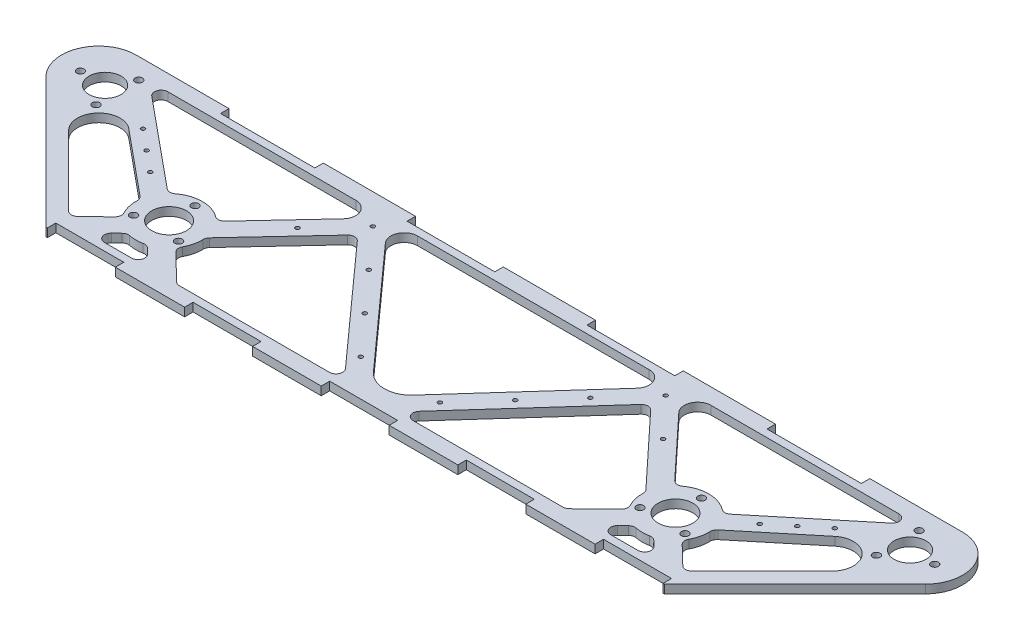
SolidWorks part; units mm, degrees
material "6061-T6 (SS)"
ref_plane "Alzado" through (0, 0, 0) normal (0, 0, 1) x (1, 0, 0)
ref_plane "Planta" through (0, 0, 0) normal (0, 1, 0) x (1, 0, 0)
ref_plane "Vista lateral" through (0, 0, 0) normal (1, 0, 0) x (0, 0, -1)
sketch "Sketch1" plane through (0, 0, 0) normal (0, 1, 0) x (1, 0, 0)
  line L0 (-232.01, 0) -> (232.01, 0)
  line L1 (-232.01, 0) -> (-329.8939, 97.8839)
  line L2 (-310.0879, 145.7) -> (310.0879, 145.7)
  line L3 (329.8939, 97.8839) -> (232.01, 0)
  line L4 (-310.0879, 135.7) -> (310.0879, 135.7) construction
  line L5 (322.8229, 104.955) -> (227.8679, 10) construction
  line L6 (-227.8679, 10) -> (227.8679, 10) construction
  line L7 (-227.8679, 10) -> (-322.8229, 104.955) construction
  arc A0 (310.0879, 145.7) -> (329.8939, 97.8839) centre (310.0879, 117.69) cw
  arc A1 (-329.8939, 97.8839) -> (-310.0879, 145.7) centre (-310.0879, 117.69) cw
  arc A2 (310.0879, 135.7) -> (322.8229, 104.955) centre (310.0879, 117.69) cw construction
  arc A3 (-322.8229, 104.955) -> (-310.0879, 135.7) centre (-310.0879, 117.69) cw construction
  point P4 (0, 0)
  dimension "D4" = 28.01
  dimension "D1" = 45
  dimension "D2" = 464.02
  dimension "D3" = 145.7
  dimension "D5" = 10
extrude "Boss-Extrude1" add sketch "Sketch1" along normal blind 6.35
sketch "Sketch2" plane through (0, 6.35, 0) normal (0, 1, 0) x (1, 0, 0)
  line L0 (310.0879, 145.7) -> (-310.0879, 145.7) construction
  line L1 (0, 0) -> (0, 145.7) construction
  line L2 (-232.01, 0) -> (232.01, 0) construction
  circle A0 centre (-302.0235, 114.35) radius 12
  circle A2 centre (-190, 50.35) radius 13
  circle A5 centre (-302.0235, 114.35) radius 18.5 construction
  circle A6 centre (-190, 50.35) radius 19.5 construction
  circle A7 centre (-320.5235, 114.35) radius 2.75
  circle A8 centre (-292.7735, 130.3715) radius 2.75
  circle A9 centre (-292.7735, 98.3285) radius 2.75
  circle A11 centre (-190, 69.85) radius 2.75
  circle A12 centre (-173.1125, 40.6) radius 2.75
  circle A13 centre (-206.8875, 40.6) radius 2.75
  circle A14 centre (190, 50.35) radius 19.5 construction
  circle A15 centre (302.0235, 114.35) radius 18.5 construction
  circle A16 centre (206.8875, 40.6) radius 2.75
  circle A17 centre (173.1125, 40.6) radius 2.75
  circle A18 centre (190, 69.85) radius 2.75
  circle A19 centre (292.7735, 98.3285) radius 2.75
  circle A20 centre (292.7735, 130.3715) radius 2.75
  circle A21 centre (320.5235, 114.35) radius 2.75
  circle A22 centre (190, 50.35) radius 13
  circle A23 centre (302.0235, 114.35) radius 12
  point P29 (-190, 50.35)
  point P30 (-302.0235, 114.35)
  point P49 (302.0235, 114.35)
  point P50 (190, 50.35)
  dimension "D3" = 24
  dimension "D6" = 26
  dimension "D7" = 37
  dimension "D8" = 39
  dimension "D9" = 5.5
  dimension "D11" = 3
  dimension "D2" = 31.35
  dimension "D4" = 50.35
  dimension "D5" = 42.01
  dimension "D12" = 604.047
  dimension "D10" = 3
extrude "Cut-Extrude1" cut sketch "Sketch2" against normal blind 10
sketch "Sketch4" plane through (0, 6.35, 0) normal (0, 1, 0) x (1, 0, 0)
  line L12 (229.3797, 6.35) -> (325.4038, 102.3741)
  line L13 (310.0879, 139.35) -> (-310.0879, 139.35)
  line L14 (-325.4038, 102.3741) -> (-229.3797, 6.35)
  line L15 (-229.3797, 6.35) -> (229.3797, 6.35)
  line L16 (229.3797, 6.35) -> (325.4038, 102.3741) construction
  line L17 (310.0879, 139.35) -> (-310.0879, 139.35) construction
  line L18 (-325.4038, 102.3741) -> (-229.3797, 6.35) construction
  line L19 (-229.3797, 6.35) -> (229.3797, 6.35) construction
  arc A6 (325.4038, 102.3741) -> (310.0879, 139.35) centre (310.0879, 117.69) ccw
  arc A7 (-310.0879, 139.35) -> (-325.4038, 102.3741) centre (-310.0879, 117.69) ccw
  arc A8 (325.4038, 102.3741) -> (310.0879, 139.35) centre (310.0879, 117.69) ccw construction
  arc A9 (-310.0879, 139.35) -> (-325.4038, 102.3741) centre (-310.0879, 117.69) ccw construction
  dimension "D1" = 6.35
sketch "Sketch3" plane through (0, 6.35, 0) normal (0, 1, 0) x (1, 0, 0)
  line L0 (-203.6098, 20.5948) -> (-199.5103, 24.558)
  line L1 (-180.4897, 24.558) -> (-176.3902, 20.5948)
  line L2 (-216.7974, 55.3714) -> (-264.9333, 95.0444)
  line L3 (-226.9661, 18.8783) -> (-212.9059, 32.4713)
  line L4 (-211.3773, 70.3424) -> (-277.5023, 124.8416)
  line L5 (-274.3223, 133.7) -> (-133.2758, 133.7)
  line L6 (-168.6307, 71.1511) -> (-125.9643, 116.8778)
  line L7 (0, 12) -> (0, 133.7) construction
  line L8 (-94.3432, 117.0171) -> (-14.878, 28.5613)
  line L9 (227.0394, 12) -> (321.4087, 106.3692)
  line L10 (310.0879, 133.7) -> (-310.0879, 133.7)
  line L11 (-321.4087, 106.3692) -> (-227.0394, 12)
  line L12 (-227.0394, 12) -> (227.0394, 12)
  line L13 (227.0394, 12) -> (321.4087, 106.3692) construction
  line L14 (310.0879, 133.7) -> (133.2758, 133.7) construction
  line L15 (-321.4087, 106.3692) -> (-227.0394, 12) construction
  line L16 (-227.0394, 12) -> (227.0394, 12) construction
  line L17 (-167.0941, 32.4713) -> (-147.3727, 13.4052)
  line L18 (-163.6645, 54.4864) -> (-113.7257, 108.0071)
  line L19 (-106.3504, 107.9375) -> (-27.6576, 20.3415)
  line L20 (-286.4232, 71.3837) -> (-233.977, 18.9375)
  line L21 (-200.1345, 12) -> (-179.8655, 12)
  line L22 (-143.8974, 12) -> (-31.3771, 12)
  line L23 (-86.9042, 133.7) -> (86.9042, 133.7)
  line L24 (143.8974, 12) -> (31.3771, 12)
  line L25 (200.1345, 12) -> (179.8655, 12)
  line L26 (286.4232, 71.3837) -> (233.977, 18.9375)
  line L27 (106.3504, 107.9375) -> (27.6576, 20.3415)
  line L28 (163.6645, 54.4864) -> (113.7257, 108.0071)
  line L29 (167.0941, 32.4713) -> (147.3727, 13.4052)
  line L30 (94.3432, 117.0171) -> (14.878, 28.5613)
  line L31 (168.6307, 71.1511) -> (125.9643, 116.8778)
  line L32 (274.3223, 133.7) -> (133.2758, 133.7)
  line L33 (211.3773, 70.3424) -> (277.5023, 124.8416)
  line L34 (226.9661, 18.8783) -> (212.9059, 32.4713)
  line L35 (216.7974, 55.3714) -> (264.9333, 95.0444)
  line L36 (180.4897, 24.558) -> (176.3902, 20.5948)
  line L37 (203.6098, 20.5948) -> (199.5103, 24.558)
  line L38 (-133.2758, 133.7) -> (-310.0879, 133.7) construction
  line L39 (86.9042, 133.7) -> (-86.9042, 133.7) construction
  arc A0 (-214.9812, 51.3192) -> (-211.9843, 38.4467) centre (-190, 50.35) ccw
  arc A1 (-264.9333, 95.0444) -> (-286.4232, 71.3837) centre (-275.1095, 82.6975) ccw
  arc A2 (-277.5023, 124.8416) -> (-274.3223, 133.7) centre (-274.3223, 128.7) cw
  arc A3 (-175.2387, 70.5268) -> (-205.1644, 70.2256) centre (-190, 50.35) ccw
  arc A4 (321.4087, 106.3692) -> (310.0879, 133.7) centre (310.0879, 117.69) ccw
  arc A5 (-310.0879, 133.7) -> (-321.4087, 106.3692) centre (-310.0879, 117.69) ccw
  arc A6 (321.4087, 106.3692) -> (310.0879, 133.7) centre (310.0879, 117.69) ccw construction
  arc A7 (-310.0879, 133.7) -> (-321.4087, 106.3692) centre (-310.0879, 117.69) ccw construction
  arc A8 (-168.0157, 38.4467) -> (-165.0073, 50.9544) centre (-190, 50.35) ccw
  arc A9 (-195.0292, 25.8611) -> (-184.9708, 25.8611) centre (-190, 50.35) ccw
  arc A10 (195.0292, 25.8611) -> (184.9708, 25.8611) centre (190, 50.35) cw
  arc A11 (168.0157, 38.4467) -> (165.0073, 50.9544) centre (190, 50.35) cw
  arc A12 (175.2387, 70.5268) -> (205.1644, 70.2256) centre (190, 50.35) cw
  arc A13 (277.5023, 124.8416) -> (274.3223, 133.7) centre (274.3223, 128.7) ccw
  arc A14 (264.9333, 95.0444) -> (286.4232, 71.3837) centre (275.1095, 82.6975) cw
  arc A15 (214.9812, 51.3192) -> (211.9843, 38.4467) centre (190, 50.35) cw
  arc A16 (-133.2758, 133.7) -> (-125.9643, 116.8778) centre (-133.2758, 123.7) cw
  arc A17 (-94.3432, 117.0171) -> (-86.9042, 133.7) centre (-86.9042, 123.7) cw
  arc A18 (94.3432, 117.0171) -> (86.9042, 133.7) centre (86.9042, 123.7) ccw
  arc A19 (125.9643, 116.8778) -> (133.2758, 133.7) centre (133.2758, 123.7) cw
  arc A20 (-175.2387, 70.5268) -> (-168.6307, 71.1511) centre (-172.2865, 74.5622) ccw
  arc A21 (-211.3773, 70.3424) -> (-205.1644, 70.2256) centre (-208.1973, 74.2008) ccw
  arc A22 (-216.7974, 55.3714) -> (-214.9812, 51.3192) centre (-219.9774, 51.513) cw
  arc A23 (-212.9059, 32.4713) -> (-211.9843, 38.4467) centre (-216.3812, 36.066) ccw
  arc A24 (-226.9661, 18.8783) -> (-233.977, 18.9375) centre (-230.4414, 22.4731) cw
  arc A25 (-203.6098, 20.5948) -> (-200.1345, 12) centre (-200.1345, 17) ccw
  arc A26 (-199.5103, 24.558) -> (-195.0292, 25.8611) centre (-196.035, 20.9633) cw
  arc A27 (-180.4897, 24.558) -> (-184.9708, 25.8611) centre (-183.965, 20.9633) ccw
  arc A28 (-176.3902, 20.5948) -> (-179.8655, 12) centre (-179.8655, 17) cw
  arc A29 (-113.7257, 108.0071) -> (-106.3504, 107.9375) centre (-110.0699, 104.596) cw
  arc A30 (-163.6645, 54.4864) -> (-165.0073, 50.9544) centre (-160.0088, 51.0753) ccw
  arc A31 (-167.0941, 32.4713) -> (-168.0157, 38.4467) centre (-163.6188, 36.066) cw
  arc A32 (-147.3727, 13.4052) -> (-143.8974, 12) centre (-143.8974, 17) ccw
  arc A33 (179.8655, 12) -> (176.3902, 20.5948) centre (179.8655, 17) cw
  arc A34 (184.9708, 25.8611) -> (180.4897, 24.558) centre (183.965, 20.9633) ccw
  arc A35 (195.0292, 25.8611) -> (199.5103, 24.558) centre (196.035, 20.9633) cw
  arc A36 (200.1345, 12) -> (203.6098, 20.5948) centre (200.1345, 17) ccw
  arc A37 (233.977, 18.9375) -> (226.9661, 18.8783) centre (230.4414, 22.4731) cw
  arc A38 (214.9812, 51.3192) -> (216.7974, 55.3714) centre (219.9774, 51.513) cw
  arc A39 (211.9843, 38.4467) -> (212.9059, 32.4713) centre (216.3812, 36.066) ccw
  arc A40 (175.2387, 70.5268) -> (168.6307, 71.1511) centre (172.2865, 74.5622) cw
  arc A41 (205.1644, 70.2256) -> (211.3773, 70.3424) centre (208.1973, 74.2008) ccw
  arc A42 (106.3504, 107.9375) -> (113.7257, 108.0071) centre (110.0699, 104.596) cw
  arc A43 (165.0073, 50.9544) -> (163.6645, 54.4864) centre (160.0088, 51.0753) ccw
  arc A44 (168.0157, 38.4467) -> (167.0941, 32.4713) centre (163.6188, 36.066) cw
  arc A45 (143.8974, 12) -> (147.3727, 13.4052) centre (143.8974, 17) ccw
  arc A46 (31.3771, 12) -> (27.6576, 20.3415) centre (31.3771, 17) cw
  arc A47 (-27.6576, 20.3415) -> (-31.3771, 12) centre (-31.3771, 17) cw
  arc A49 (-14.878, 28.5613) -> (14.878, 28.5613) centre (0, 41.9271) ccw
  point P72 (-171.9247, 67.6209)
  point P75 (-208.0753, 67.6209)
  point P78 (-214.774, 53.7038)
  point P81 (-209.9698, 35.3098)
  point P84 (-230.5007, 15.4612)
  point P87 (-212.5, 12)
  point P90 (-197.5, 26.5015)
  point P93 (-182.5, 26.5015)
  point P96 (-167.5, 12)
  point P99 (-110, 112)
  point P102 (-165.1318, 52.9138)
  point P105 (-170.0302, 35.3098)
  point P108 (-145.9191, 12)
  point P111 (167.5, 12)
  point P114 (182.5, 26.5015)
  point P117 (197.5, 26.5015)
  point P120 (212.5, 12)
  point P123 (230.5007, 15.4612)
  point P126 (214.774, 53.7038)
  point P129 (209.9698, 35.3098)
  point P132 (171.9247, 67.6209)
  point P135 (208.0753, 67.6209)
  point P138 (110, 112)
  point P141 (165.1318, 52.9138)
  point P144 (170.0302, 35.3098)
  point P147 (145.9191, 12)
  point P150 (20.164, 12)
  point P153 (-20.164, 12)
  dimension "D2" = 50
  dimension "D3" = 5
  dimension "D4" = 15
  dimension "D11" = 18.394
  dimension "D8" = 16
  dimension "D15" = 10
  dimension "D16" = 10
  dimension "D17" = 10
  dimension "D18" = 10
  dimension "D20" = 5
  dimension "D21" = 20
  dimension "D5" = 15
  dimension "D6" = 15
  dimension "D7" = 45
  dimension "D9" = 220
  dimension "D10" = 15
  dimension "D12" = 15
  dimension "D13" = 15
  dimension "D14" = 65
  dimension "D19" = 100
  dimension "D1" = 12
extrude "Cut-Extrude4" cut sketch "Sketch3" against normal blind 10
sketch "Sketch5" plane through (0, 6.35, 0) normal (0, 1, 0) x (1, 0, 0)
  line L0 (-232.01, 0) -> (232.01, 0) construction
  line L1 (-231.01, 0) -> (232.01, 0) construction
  line L2 (-231.01, 0) -> (-231.01, 6.36) construction
  line L3 (-231.01, 6.36) -> (232.01, 6.36) construction
  line L4 (232.01, 0) -> (232.01, 6.36) construction
  line L5 (-231.01, 6.36) -> (-180.01, 6.36)
  line L6 (-231.01, 6.36) -> (-231.01, 0)
  line L7 (-231.01, 0) -> (-180.01, 0)
  line L8 (-180.01, 6.36) -> (-180.01, 0)
  line L9 (-25.5, 6.36) -> (25.5, 6.36)
  line L10 (-25.5, 6.36) -> (-25.5, 0)
  line L11 (-25.5, 0) -> (25.5, 0)
  line L12 (25.5, 6.36) -> (25.5, 0)
  line L13 (-128.01, 6.36) -> (-77.01, 6.36)
  line L14 (-128.01, 6.36) -> (-128.01, 0)
  line L15 (-128.01, 0) -> (-77.01, 0)
  line L16 (-77.01, 6.36) -> (-77.01, 0)
  line L17 (0, 0) -> (0, 6.36) construction
  line L23 (77.01, 6.36) -> (128.01, 6.36)
  line L24 (77.01, 6.36) -> (77.01, 0)
  line L25 (77.01, 0) -> (128.01, 0)
  line L26 (128.01, 6.36) -> (128.01, 0)
  line L27 (180.01, 6.36) -> (231.01, 6.36)
  line L28 (180.01, 6.36) -> (180.01, 0)
  line L29 (180.01, 0) -> (231.01, 0)
  line L30 (231.01, 6.36) -> (231.01, 0)
  dimension "D1" = 6.36
  dimension "D2" = 51
  dimension "D3" = 51
  dimension "D4" = 25.5
  dimension "D5" = 51
  dimension "D6" = 52
  dimension "D7" = 51.51
  dimension "D8" = 51
  dimension "D9" = 51
  dimension "D10" = 1
  dimension "D11" = 51.51
  dimension "D12" = 1
  dimension "D13" = 52
extrude "Cut-Extrude5" cut sketch "Sketch5" against normal blind 10
sketch "Sketch6" plane through (0, 6.35, 0) normal (0, 1, 0) x (1, 0, 0)
  line L0 (-309.99, 139.34) -> (309.99, 139.34) construction
  line L1 (310.0879, 145.7) -> (-310.0879, 145.7) construction
  line L3 (-309.99, 139.34) -> (-239.99, 139.34) construction
  line L4 (-309.99, 139.34) -> (-309.99, 145.7) construction
  line L5 (-309.99, 145.7) -> (-239.99, 145.7) construction
  line L6 (-239.99, 139.34) -> (-239.99, 145.7) construction
  line L7 (-309.99, 139.34) -> (-239.99, 145.7) construction
  line L8 (-309.99, 145.7) -> (-239.99, 139.34) construction
  line L9 (-169.99, 145.7) -> (-99.99, 145.7) construction
  line L10 (-169.99, 145.7) -> (-169.99, 139.34) construction
  line L11 (-169.99, 139.34) -> (-99.99, 139.34) construction
  line L12 (-99.99, 145.7) -> (-99.99, 139.34) construction
  line L13 (-169.99, 145.7) -> (-99.99, 139.34) construction
  line L14 (-169.99, 139.34) -> (-99.99, 145.7) construction
  line L15 (-35, 145.7) -> (35, 145.7) construction
  line L16 (-35, 145.7) -> (-35, 139.34) construction
  line L17 (-35, 139.34) -> (35, 139.34) construction
  line L18 (35, 145.7) -> (35, 139.34) construction
  line L19 (-35, 145.7) -> (35, 139.34) construction
  line L20 (-35, 139.34) -> (35, 145.7) construction
  line L21 (310.0879, 145.7) -> (240.0879, 145.7) construction
  line L22 (310.0879, 145.7) -> (310.0879, 139.34) construction
  line L23 (310.0879, 139.34) -> (240.0879, 139.34) construction
  line L24 (240.0879, 145.7) -> (240.0879, 139.34) construction
  line L25 (310.0879, 145.7) -> (240.0879, 139.34) construction
  line L26 (310.0879, 139.34) -> (240.0879, 145.7) construction
  line L27 (170.0879, 145.7) -> (100.0879, 145.7) construction
  line L28 (170.0879, 145.7) -> (170.0879, 139.34) construction
  line L29 (170.0879, 139.34) -> (100.0879, 139.34) construction
  line L30 (100.0879, 145.7) -> (100.0879, 139.34) construction
  line L31 (170.0879, 145.7) -> (100.0879, 139.34) construction
  line L32 (170.0879, 139.34) -> (100.0879, 145.7) construction
  line L33 (-240.39, 145.7) -> (-169.59, 145.7)
  line L34 (-240.39, 145.7) -> (-240.39, 139.34)
  line L35 (-240.39, 139.34) -> (-169.59, 139.34)
  line L36 (-169.59, 145.7) -> (-169.59, 139.34)
  line L37 (-240.39, 145.7) -> (-169.59, 139.34) construction
  line L38 (-240.39, 139.34) -> (-169.59, 145.7) construction
  line L39 (-100.39, 145.7) -> (-34.6, 145.7)
  line L40 (-100.39, 145.7) -> (-100.39, 139.34)
  line L41 (-100.39, 139.34) -> (-34.6, 139.34)
  line L42 (-34.6, 145.7) -> (-34.6, 139.34)
  line L43 (-100.39, 145.7) -> (-34.6, 139.34) construction
  line L44 (-100.39, 139.34) -> (-34.6, 145.7) construction
  line L45 (34.6, 145.7) -> (100.4879, 145.7)
  line L46 (34.6, 145.7) -> (34.6, 139.34)
  line L47 (34.6, 139.34) -> (100.4879, 139.34)
  line L48 (100.4879, 145.7) -> (100.4879, 139.34)
  line L49 (34.6, 145.7) -> (100.4879, 139.34) construction
  line L50 (34.6, 139.34) -> (100.4879, 145.7) construction
  line L51 (169.6879, 145.7) -> (240.4879, 145.7)
  line L52 (169.6879, 145.7) -> (169.6879, 139.34)
  line L53 (169.6879, 139.34) -> (240.4879, 139.34)
  line L54 (240.4879, 145.7) -> (240.4879, 139.34)
  line L55 (169.6879, 145.7) -> (240.4879, 139.34) construction
  line L56 (169.6879, 139.34) -> (240.4879, 145.7) construction
  point P3 (0, 139.34)
  point P11 (-274.99, 142.52)
  point P14 (-134.99, 142.52)
  point P19 (0, 142.52)
  point P25 (275.0879, 142.52)
  point P30 (135.0879, 142.52)
  point P35 (-204.99, 142.52)
  point P40 (-67.495, 142.52)
  point P45 (67.5439, 142.52)
  point P50 (205.0879, 142.52)
  dimension "D1" = 6.36
  dimension "D2" = 70
  dimension "D3" = 70
  dimension "D4" = 70
  dimension "D5" = 70
  dimension "D6" = 619.98
  dimension "D7" = 70
  dimension "D8" = 70
  dimension "D9" = 70
  dimension "D10" = 0.4
  dimension "D11" = 0.4
  dimension "D12" = 0.4
  dimension "D13" = 0.4
  dimension "D14" = 0.4
  dimension "D15" = 0.4
  dimension "D16" = 0.4
  dimension "D17" = 0.4
extrude "Cut-Extrude6" cut sketch "Sketch6" against normal blind 10
sketch "Sketch7" plane through (0, 6.35, 0) normal (0, 1, 0) x (1, 0, 0)
  line L0 (-169.59, 145.7) -> (-169.59, 185.7)
  line L1 (-149.59, 185.7) -> (-149.59, 145.7)
  line L2 (-100.39, 145.7) -> (-169.59, 145.7) construction
  line L3 (-159.59, 185.7) -> (-159.59, 155.7) construction
  line L4 (-156.59, 185.7) -> (-156.59, 155.7)
  line L5 (-162.59, 185.7) -> (-162.59, 155.7)
  line L6 (-169.59, 145.7) -> (-149.59, 145.7)
  arc A0 (-169.59, 185.7) -> (-149.59, 185.7) centre (-159.59, 185.7) cw
  arc A1 (-156.59, 185.7) -> (-162.59, 185.7) centre (-159.59, 185.7) ccw
  arc A2 (-162.59, 155.7) -> (-156.59, 155.7) centre (-159.59, 155.7) ccw
  point P5 (-159.59, 170.7)
  dimension "D1" = 20
  dimension "D2" = 40
  dimension "D3" = 6
  dimension "D4" = 30
extrude "Boss-Extrude2" [suppressed] add sketch "Sketch7" against normal through all
mirror "Mirror1" [suppressed] about plane through (0, 0, 0) normal (1, 0, 0)
sketch "Sketch8" plane through (0, 6.35, 0) normal (0, 1, 0) x (1, 0, 0)
  circle A0 centre (259.5529, 100.3289) radius 1.5
  circle A1 centre (244.1193, 87.6088) radius 1.5
  circle A2 centre (228.6856, 74.8886) radius 1.5
  circle A3 centre (137.1838, 93.86) radius 1.5
  circle A4 centre (109.8951, 123.1059) radius 1.5
  circle A5 centre (83.1635, 93.3499) radius 1.5
  circle A6 centre (56.4319, 63.5939) radius 1.5
  circle A7 centre (29.7003, 33.8379) radius 1.5
  circle A8 centre (-29.7003, 33.8379) radius 1.5
  circle A9 centre (-56.4319, 63.5939) radius 1.5
  circle A10 centre (-83.1635, 93.3499) radius 1.5
  circle A11 centre (-109.8951, 123.1059) radius 1.5
  circle A12 centre (-137.1838, 93.86) radius 1.5
  circle A13 centre (-228.6856, 74.8886) radius 1.5
  circle A14 centre (-244.1193, 87.6088) radius 1.5
  circle A15 centre (-259.5529, 100.3289) radius 1.5
  dimension "D1" = 3
extrude "Cut-Extrude7" cut sketch "Sketch8" against normal up to surface (6.35 mm away) up to face at (0.014, 0, -67.7219)
